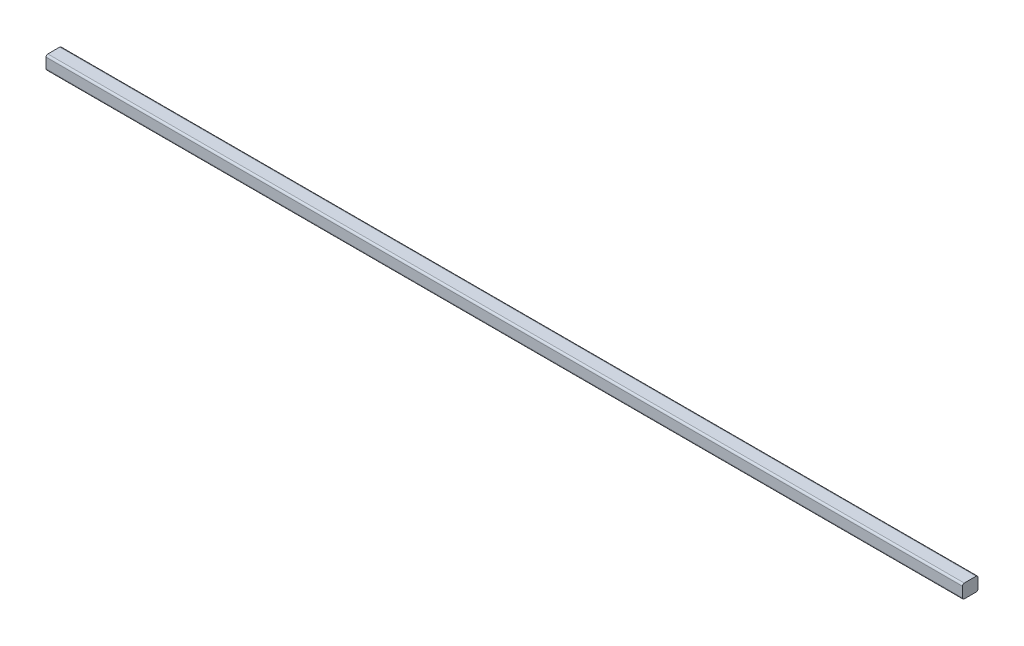
SolidWorks part; units mm, degrees
ref_plane "Front Plane" through (0, 0, 0) normal (0, 0, 1) x (1, 0, 0)
ref_plane "Top Plane" through (0, 0, 0) normal (0, 1, 0) x (1, 0, 0)
ref_plane "Right Plane" through (0, 0, 0) normal (1, 0, 0) x (0, 0, -1)
sketch "Sketch3" plane through (0, 0, 0) normal (1, 0, 0) x (0, 0, -1)
  line L1 (4.25, -3.75) -> (-4.25, -3.75)
  line L2 (4.25, -3.75) -> (4.25, 3.75)
  line L3 (4.25, 3.75) -> (-4.25, 3.75)
  line L4 (-4.25, -3.75) -> (-4.25, 3.75)
  line L5 (4.25, -3.75) -> (-4.25, 3.75) construction
  line L6 (4.25, 3.75) -> (-4.25, -3.75) construction
  point P0 (0, 0)
  dimension "D1" = 8.5
  dimension "D2" = 7.5
extrude "Boss-Extrude1" add sketch "Sketch3" along normal blind 500
fillet "Fillet2" radius 1 4 edges at (250, 3.75, -4.25) (250, -3.75, -4.25) (250, 3.75, 4.25) (250, -3.75, 4.25)
